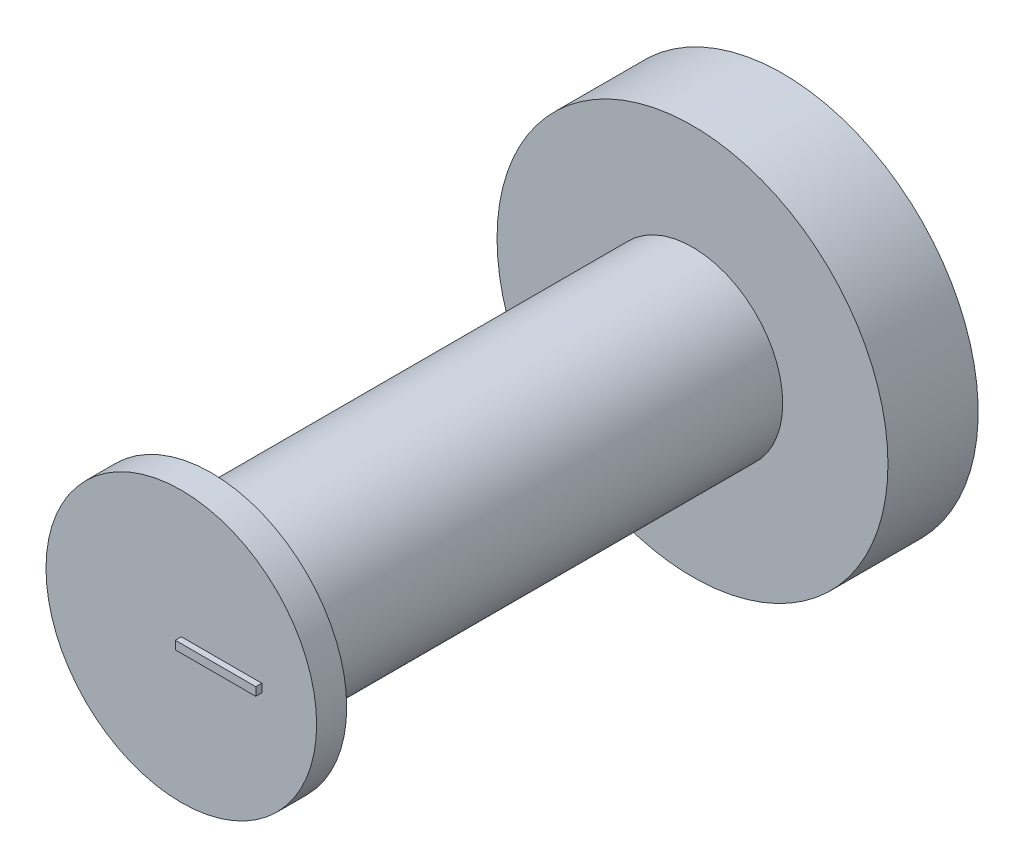
SolidWorks part; units mm, degrees
ref_plane "前视基准面" through (0, 0, 0) normal (0, 0, 1) x (1, 0, 0)
ref_plane "上视基准面" through (0, 0, 0) normal (0, 1, 0) x (1, 0, 0)
ref_plane "右视基准面" through (0, 0, 0) normal (1, 0, 0) x (0, 0, -1)
sketch "草图1" plane through (0, 0, 0) normal (0, 0, 1) x (1, 0, 0)
  circle A0 centre (0, 0) radius 80
  dimension "D1" = 160
extrude "凸台-拉伸1" add sketch "草图1" along normal blind 30
sketch "草图2" plane through (0, 0, 30) normal (0, 0, 1) x (1, 0, 0)
  circle A0 centre (0, 0) radius 30
  dimension "D1" = 60
extrude "凸台-拉伸2" add sketch "草图2" along normal blind 160
sketch "草图3" plane through (0, 0, 190) normal (0, 0, 1) x (1, 0, 0)
  circle A0 centre (0, 0) radius 45
  dimension "D1" = 90
extrude "凸台-拉伸3" add sketch "草图3" along normal blind 10
sketch "草图5" plane through (0, 0, 200) normal (0, 0, 1) x (1, 0, 0)
  line L1 (0, 0) -> (26.7574, 0)
  line L2 (0, 0) -> (0, 2.7736)
  line L3 (0, 2.7736) -> (26.7574, 2.7736)
  line L4 (26.7574, 0) -> (26.7574, 2.7736)
extrude "凸台-拉伸6" add sketch "草图5" along normal blind 2
sketch "草图6" plane through (0, 0, 0) normal (0, 0, -1) x (-1, 0, 0)
  circle A0 centre (0, 0) radius 65
  circle A1 centre (0, 0) radius 97.7795
extrude "切除-拉伸1" cut sketch "草图6" against normal blind 42
scale "缩放比例2" scale about origin uniform scaling yes scale factor 0.345
